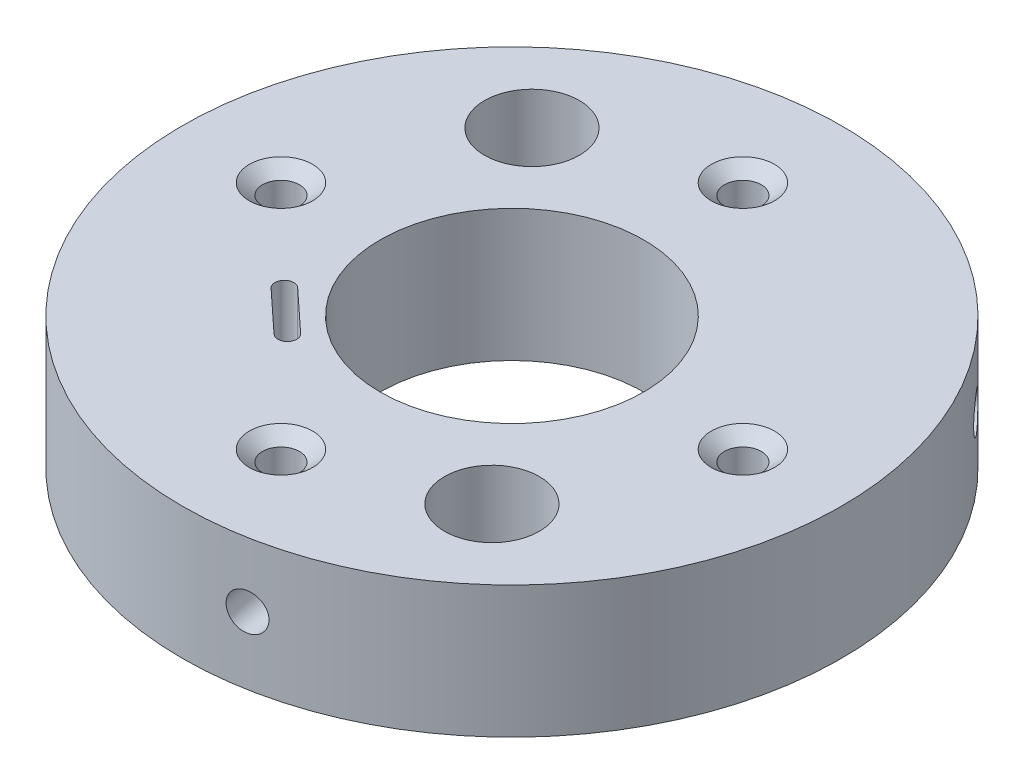
SolidWorks part; units mm, degrees
ref_plane "Front Plane" through (0, 0, 0) normal (0, 0, 1) x (1, 0, 0)
ref_plane "Top Plane" through (0, 0, 0) normal (0, 1, 0) x (1, 0, 0)
ref_plane "Right Plane" through (0, 0, 0) normal (1, 0, 0) x (0, 0, -1)
sketch "Sketch1" plane through (0, 0, 0) normal (0, 1, 0) x (1, 0, 0)
  circle A0 centre (0, 0) radius 15.875
  dimension "D1" = 31.75
extrude "Boss-Extrude1" add sketch "Sketch1" along normal blind 6.35
sketch "Sketch2" plane through (0, 6.35, 0) normal (0, 1, 0) x (1, 0, 0)
  circle A0 centre (0, 0) radius 6.35
  dimension "D1" = 12.7
extrude "Cut-Extrude1" cut sketch "Sketch2" against normal through all
sketch "Sketch5" plane through (0, 6.35, 0) normal (0, 1, 0) x (1, 0, 0)
  line L0 (0, 0) -> (0, 11.1252)
  line L1 (0, 0) -> (11.1252, 0)
  dimension "D1" = 11.1252
  dimension "D2" = 11.1252
hole_wizard "Tap Drill for #2-56 Tap2" positions "Sketch6" profile "Sketch7" hole size "#2-56" standard "ANSI Inch" end condition through all
sketch "Sketch6" plane through (0, 6.35, 0) normal (0, 1, 0) x (1, 0, 0)
  point P0 (0, 11.1252)
sketch "Sketch7" plane through (0, 6.35, -11.1252) normal (1, 0, 0) x (0, 0, 1)
  line L0 (0, 0) -> (0, 6.35)
  line L1 (0, 6.35) -> (0.889, 6.35)
  line L2 (0.889, 6.35) -> (0.889, 0.5328)
  line L3 (0.889, 0.5328) -> (1.524, 0)
  line L5 (1.524, 0) -> (0, 0)
  line L6 (-0.889, 0.5328) -> (-1.524, 0) construction
  line L11 (0, -6.35) -> (0, 107.95) construction
  dimension "Thru Hole Dia." = 1.778
  dimension "Thru Hole Depth" = 6.35
  dimension "Near C'Sink Dia." = 3.048
  dimension "Near C'Sink Angle" = 100
pattern_circular "CirPattern1" count 2 every 180 about axis through (0, 0, 0) along (0, 1, 0) of "Tap Drill for #2-56 Tap2"
hole_wizard "Tap Drill for #2-56 Tap1" positions "Sketch9" profile "Sketch10" hole size "#2-56" standard "ANSI Inch"
sketch "Sketch9" plane through (0, 6.35, 0) normal (0, 1, 0) x (1, 0, 0)
  point P0 (11.1252, 0)
sketch "Sketch10" plane through (11.1252, 6.35, 0) normal (1, 0, 0) x (0, 0, 1)
  line L0 (0, 0) -> (0, 4.3442)
  line L1 (0, 4.3442) -> (0.889, 3.81)
  line L2 (0.889, 3.81) -> (0.889, 0.5328)
  line L3 (0.889, 0.5328) -> (1.524, 0)
  line L5 (1.524, 0) -> (0, 0)
  line L6 (-0.889, 0.5328) -> (-1.524, 0) construction
  line L10 (0, 4.3442) -> (-0.889, 3.81) construction
  line L11 (0, -6.35) -> (0, 107.95) construction
  dimension "Hole Dia." = 1.778
  dimension "Hole Depth" = 3.81
  dimension "Near C'Sink Dia." = 3.048
  dimension "Near C'Sink Angle" = 100
  dimension "Drill Angle" = 118
pattern_circular "CirPattern2" count 2 over 360 about axis through (0, 0, 0) along (0, 1, 0) of "Tap Drill for #2-56 Tap1"
sketch "Sketch11" plane through (0, 6.35, 0) normal (0, 1, 0) x (1, 0, 0)
  line L0 (0, 0) -> (-7.3609, 8.325)
  circle A0 centre (-7.3609, 8.325) radius 2.286
  dimension "D2" = 4.572
  dimension "D1" = 11.1125
extrude "Cut-Extrude2" cut sketch "Sketch11" against normal through all contours A0
pattern_circular "CirPattern3" count 2 over 360 about axis through (0, 0, 0) along (0, 1, 0) of "Cut-Extrude2"
ref_plane "Plane1" through (0, 3.175, 0) normal (0, -1, 0) x (-1, 0, 0)
ref_plane "Plane2" through (0, 0, 15.875) normal (0, 0, 1) x (1, 0, 0)
hole_wizard "Tap Drill for #2-56 Tap3" positions "3DSketch1" profile "Sketch16" hole size "#2-56" standard "ANSI Inch"
sketch3d "3DSketch1"
  point P0 (12.0931, 3.245, -10.2845)
sketch "Sketch16" plane through (12.0931, 3.245, -10.2845) normal (0, 1, 0) x (-0.6478, 0, -0.7618)
  line L0 (0, 0) -> (0, 7.096)
  line L1 (0, 7.096) -> (0.889, 6.35)
  line L2 (0.889, 6.35) -> (0.889, 0)
  line L5 (0.889, 0) -> (0, 0)
  line L10 (0, 7.096) -> (-0.889, 6.35) construction
  line L11 (0, -6.35) -> (0, 107.95) construction
  dimension "Hole Dia." = 1.778
  dimension "Hole Depth" = 6.35
  dimension "Drill Angle" = 100
pattern_circular "CirPattern4" count 3 every 120 about axis through (0, 6.35, 0) along (0, -1, 0) of "Tap Drill for #2-56 Tap3"
sketch "Sketch17" plane through (0, 6.35, 0) normal (0, 1, 0) x (1, 0, 0)
  line L0 (-4.6609, -6.1577) -> (-6.6475, -4.3143) construction
  line L1 (-4.9691, -6.4899) -> (-6.9558, -4.6465)
  line L2 (-4.3526, -5.8255) -> (-6.3392, -3.982)
  arc A0 (-4.9691, -6.4899) -> (-4.3526, -5.8255) centre (-4.6609, -6.1577) ccw
  arc A1 (-6.3392, -3.982) -> (-6.9558, -4.6465) centre (-6.6475, -4.3143) ccw
  point P4 (-5.6542, -5.236)
extrude "Cut-Extrude3" cut sketch "Sketch17" against normal through all
